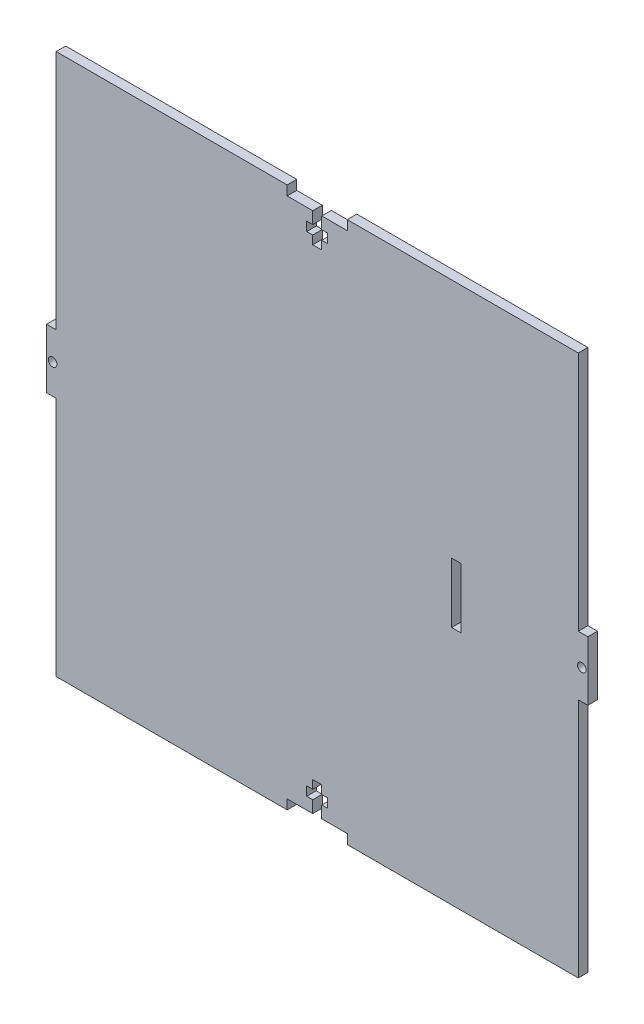
SolidWorks part; units mm, degrees
ref_plane "Front Plane" through (0, 0, 0) normal (0, 0, 1) x (1, 0, 0)
ref_plane "Top Plane" through (0, 0, 0) normal (0, 1, 0) x (1, 0, 0)
ref_plane "Right Plane" through (0, 0, 0) normal (1, 0, 0) x (0, 0, -1)
sketch "Sketch3" plane through (0, 0, 0) normal (0, 0, 1) x (1, 0, 0)
  line L0 (-90, 0) -> (90, 0) construction
  line L1 (-90, 90) -> (90, 90)
  line L2 (-90, 90) -> (-90, -90)
  line L3 (-90, -90) -> (90, -90)
  line L4 (90, 90) -> (90, -90)
  line L5 (-90, 0) -> (42.6717, 0) construction
  line L6 (0, 90) -> (0, -90) construction
  line L8 (47.8597, -10.125) -> (44.6797, -10.125)
  line L9 (47.8597, -10.125) -> (47.8597, 9.875)
  line L10 (47.8597, 9.875) -> (44.6797, 9.875)
  line L11 (44.6797, -10.125) -> (44.6797, 9.875)
  dimension "D1" = 180
  dimension "D3" = 180
extrude "Boss-Extrude1" add sketch "Sketch3" along normal blind 3.18
sketch "Sketch4" plane through (0, 0, 3.18) normal (0, 0, 1) x (1, 0, 0)
  line L0 (-90, 90) -> (-90, -90) construction
  line L1 (90, -90) -> (90, 90) construction
  line L2 (-90, 0) -> (90, 0) construction
  line L3 (0.9399, -90) -> (0, -90) construction
  line L4 (90, 90) -> (-90, 90) construction
  line L5 (0, -90) -> (0, 90) construction
  line L6 (1.5, 86.82) -> (10, 86.82)
  line L7 (-10, 90) -> (10, 90)
  line L8 (-10, 90) -> (-10, 86.82)
  line L9 (-10, 86.82) -> (-1.5, 86.82)
  line L10 (10, 90) -> (10, 86.82)
  line L11 (-3.5, 82.82) -> (-1.5, 82.82)
  line L12 (-3.5, 82.82) -> (-3.5, 79.82)
  line L13 (-3.5, 79.82) -> (-1.5, 79.82)
  line L14 (3.5, 82.82) -> (3.5, 79.82)
  line L15 (1.5, 82.82) -> (3.5, 82.82)
  line L16 (-1.5, 86.82) -> (-1.5, 82.82)
  line L17 (-1.5, 77) -> (1.5, 77)
  line L18 (1.5, 86.82) -> (1.5, 82.82)
  line L19 (-90, -90) -> (90, -90) construction
  line L20 (1.5, 79.82) -> (3.5, 79.82)
  line L21 (-1.5, 79.82) -> (-1.5, 77)
  line L22 (1.5, 79.82) -> (1.5, 77)
  line L23 (1.5, -79.82) -> (1.5, -77)
  line L24 (-1.5, -79.82) -> (-1.5, -77)
  line L25 (1.5, -79.82) -> (3.5, -79.82)
  line L26 (1.5, -86.82) -> (1.5, -82.82)
  line L27 (-1.5, -77) -> (1.5, -77)
  line L28 (-1.5, -86.82) -> (-1.5, -82.82)
  line L29 (1.5, -82.82) -> (3.5, -82.82)
  line L30 (3.5, -82.82) -> (3.5, -79.82)
  line L31 (-3.5, -79.82) -> (-1.5, -79.82)
  line L32 (-3.5, -82.82) -> (-3.5, -79.82)
  line L33 (-3.5, -82.82) -> (-1.5, -82.82)
  line L34 (10, -90) -> (10, -86.82)
  line L35 (-10, -86.82) -> (-1.5, -86.82)
  line L36 (-10, -90) -> (-10, -86.82)
  line L37 (-10, -90) -> (10, -90)
  line L38 (1.5, -86.82) -> (10, -86.82)
  dimension "D1" = 20
  dimension "D2" = 3.18
  dimension "D3" = 4
  dimension "D4" = 3
  dimension "D5" = 3
  dimension "D6" = 13
  dimension "D7" = 7
sketch "Sketch5" plane through (0, 0, 3.18) normal (0, 0, 1) x (1, 0, 0)
  line L0 (-90, 0) -> (90, 0) construction
  line L1 (-90, 90) -> (-86.82, 90)
  line L2 (-90, 90) -> (-90, 9.875)
  line L3 (-90, 9.875) -> (-86.82, 9.875)
  line L4 (-86.82, 90) -> (-86.82, 9.875)
  line L5 (-90, -90) -> (-86.82, -90)
  line L6 (-90, -90) -> (-90, -9.875)
  line L7 (-90, -9.875) -> (-86.82, -9.875)
  line L8 (-86.82, -90) -> (-86.82, -9.875)
  line L9 (-90, 90) -> (-90, -90) construction
  line L10 (0, 90) -> (0, -90) construction
  line L11 (86.82, -90) -> (86.82, -9.875)
  line L12 (90, -9.875) -> (86.82, -9.875)
  line L13 (90, -90) -> (90, -9.875)
  line L14 (90, -90) -> (86.82, -90)
  line L15 (86.82, 90) -> (86.82, 9.875)
  line L16 (90, 9.875) -> (86.82, 9.875)
  line L17 (90, 90) -> (90, 9.875)
  line L18 (90, 90) -> (86.82, 90)
  circle A0 centre (-88, 0) radius 1.436
  circle A1 centre (88, 0) radius 1.436
  dimension "D4" = 2.872
  dimension "D5" = 2
  dimension "D1" = 3.18
  dimension "D2" = 3.18
  dimension "D3" = 19.75
extrude "Cut-Extrude1" cut sketch "Sketch4" against normal through all
extrude "Cut-Extrude2" cut sketch "Sketch5" against normal through all
